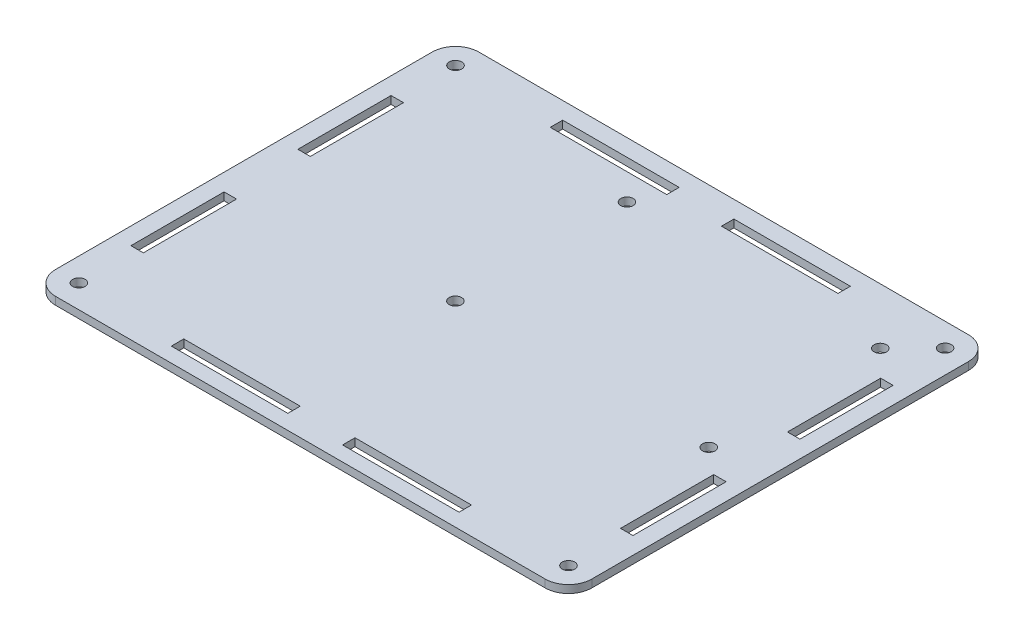
SolidWorks part; units mm, degrees
ref_plane "Front Plane" through (0, 0, 0) normal (0, 0, 1) x (1, 0, 0)
ref_plane "Top Plane" through (0, 0, 0) normal (0, 1, 0) x (1, 0, 0)
ref_plane "Right Plane" through (0, 0, 0) normal (1, 0, 0) x (0, 0, -1)
sketch "Sketch1" plane through (0, 0, 0) normal (0, 1, 0) x (1, 0, 0)
  line L0 (0, 8.1414) -> (0, -124047.6473) construction
  line L1 (0, 0) -> (138.1, 0)
  line L2 (0, 0) -> (0, 109)
  line L3 (0, 109) -> (138.1, 109)
  line L4 (138.1, 0) -> (138.1, 109)
  line L9 (3.753, 0) -> (124059.5417, 0) construction
  line L10 (12, 0) -> (12, -50000) construction
  line L11 (126.1, 0) -> (126.1, -50000) construction
  line L12 (0, 12) -> (-50000, 12) construction
  line L13 (-45.6158, 97) -> (49954.3842, 97) construction
  line L14 (-2.2542, 48) -> (-50002.2542, 48) construction
  line L15 (-71.6312, 38) -> (49928.3688, 38) construction
  line L16 (82.1, 114.3993) -> (82.1, -49885.6007) construction
  line L17 (60, 108.3918) -> (60, -49891.6082) construction
  line L18 (92.1, 117.8875) -> (92.1, -49882.1125) construction
  line L19 (32, 7.0141) -> (62, 7.0141)
  line L20 (32, 104.6) -> (62, 104.6)
  line L21 (32, 104.6) -> (32, 101.4)
  line L22 (32, 101.4) -> (62, 101.4)
  line L23 (62, 104.6) -> (62, 101.4)
  line L24 (106.1, 104.6) -> (76.1, 104.6)
  line L25 (106.1, 104.6) -> (106.1, 101.4)
  line L26 (106.1, 101.4) -> (76.1, 101.4)
  line L27 (76.1, 104.6) -> (76.1, 101.4)
  line L28 (32, 7.0141) -> (32, 3.8141)
  line L29 (32, 3.8141) -> (62, 3.8141)
  line L30 (62, 7.0141) -> (62, 3.8141)
  line L31 (106.1, 7.0141) -> (76.1, 7.0141)
  line L32 (106.1, 7.0141) -> (106.1, 3.8141)
  line L33 (106.1, 3.8141) -> (76.1, 3.8141)
  line L34 (76.1, 7.0141) -> (76.1, 3.8141)
  line L40 (4.4, 88) -> (7.6, 88)
  line L41 (4.4, 88) -> (4.4, 64)
  line L42 (4.4, 64) -> (7.6, 64)
  line L43 (7.6, 88) -> (7.6, 64)
  line L44 (4.4, 45) -> (7.6, 45)
  line L45 (4.4, 45) -> (4.4, 21)
  line L46 (4.4, 21) -> (7.6, 21)
  line L47 (7.6, 45) -> (7.6, 21)
  line L48 (130.5, 88) -> (133.7, 88)
  line L49 (130.5, 88) -> (130.5, 64)
  line L50 (130.5, 64) -> (133.7, 64)
  line L51 (133.7, 88) -> (133.7, 64)
  line L52 (130.5, 45) -> (133.7, 45)
  line L53 (130.5, 45) -> (130.5, 21)
  line L54 (130.5, 21) -> (133.7, 21)
  line L55 (133.7, 45) -> (133.7, 21)
  circle A1 centre (58.541, 94.62) radius 1.6
  circle A2 centre (123.794, 94.62) radius 1.6
  circle A3 centre (123.794, 50.439) radius 1.6
  circle A4 centre (58.541, 50.44) radius 1.6
  circle A7 centre (6, 103) radius 1.6
  circle A8 centre (132.1, 103) radius 1.6
  circle A9 centre (132.1, 6) radius 1.6
  circle A10 centre (6, 6) radius 1.6
  point P75 (0, 0)
  point P76 (132.1, 21)
  point P77 (132.1, 64)
  point P78 (32, 103)
  point P79 (0, 0)
  point P80 (0, 0)
  point P81 (0, 0)
  dimension "D14" = 65.253
  dimension "D16" = 2.439
  dimension "D22" = 6
  dimension "D24" = 6
  dimension "D26" = 6
  dimension "D28" = 6
  dimension "D1" = 109
  dimension "D2" = 138.1
  dimension "D3" = 12
  dimension "D4" = 12
  dimension "D6" = 12
  dimension "D7" = 49
  dimension "D8" = 10
  dimension "D9" = 26
  dimension "D10" = 70.1
  dimension "D11" = 48
  dimension "D12" = 10
  dimension "D13" = 34
  dimension "D15" = 2.306
  dimension "D17" = 2.44
  dimension "D18" = 2.306
  dimension "D19" = 2.38
  dimension "D23" = 6
  dimension "D25" = 6
  dimension "D27" = 6
  dimension "D29" = 6
  dimension "D30" = 30
  dimension "D31" = 20
  dimension "D32" = 3.2
  dimension "D33" = 30
  dimension "D34" = 20
  dimension "D35" = 20
  dimension "D36" = 3.2
  dimension "D37" = 20
  dimension "D38" = 30
  dimension "D39" = 30
  dimension "D40" = 24
  dimension "D41" = 9
  dimension "D42" = 19
  dimension "D43" = 24
  dimension "D44" = 24
  dimension "D45" = 24
  dimension "D46" = 9
  dimension "D47" = 19
  dimension "D48" = 3.2
  dimension "D49" = 1.6
  dimension "D50" = 3.2
  dimension "D51" = 3.2
  dimension "D52" = 14.1
  dimension "D53" = 14.1
extrude "Boss-Extrude1" add sketch "Sketch1" along normal blind 2
fillet "Fillet1" radius 6 1 edges at (0, 1, -109)
fillet "Fillet2" radius 6 1 edges at (0, 1, 0)
fillet "Fillet3" radius 6 2 edges at (138.1, 1, -109) (138.1, 1, 0)
